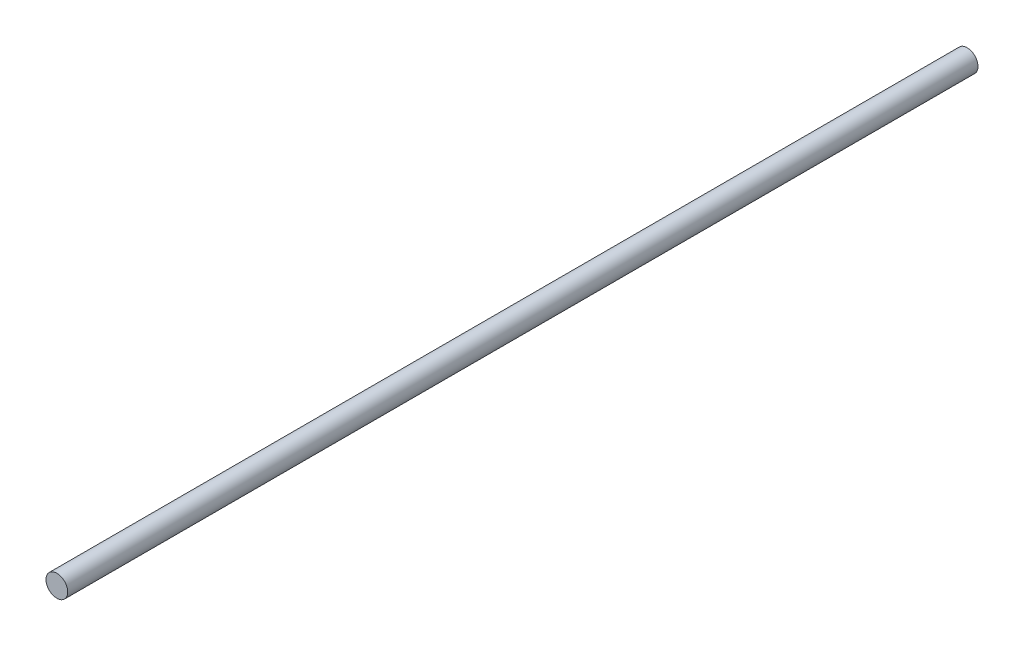
SolidWorks part; units mm, degrees
ref_plane "Front Plane" through (0, 0, 0) normal (0, 0, 1) x (1, 0, 0)
ref_plane "Top Plane" through (0, 0, 0) normal (0, 1, 0) x (1, 0, 0)
ref_plane "Right Plane" through (0, 0, 0) normal (1, 0, 0) x (0, 0, -1)
sketch "Sketch1" plane through (0, 0, 0) normal (0, 0, 1) x (1, 0, 0)
  circle A0 centre (0, 0) radius 4
  dimension "D1" = 8
extrude "Boss-Extrude1" add sketch "Sketch1" along normal blind 335
